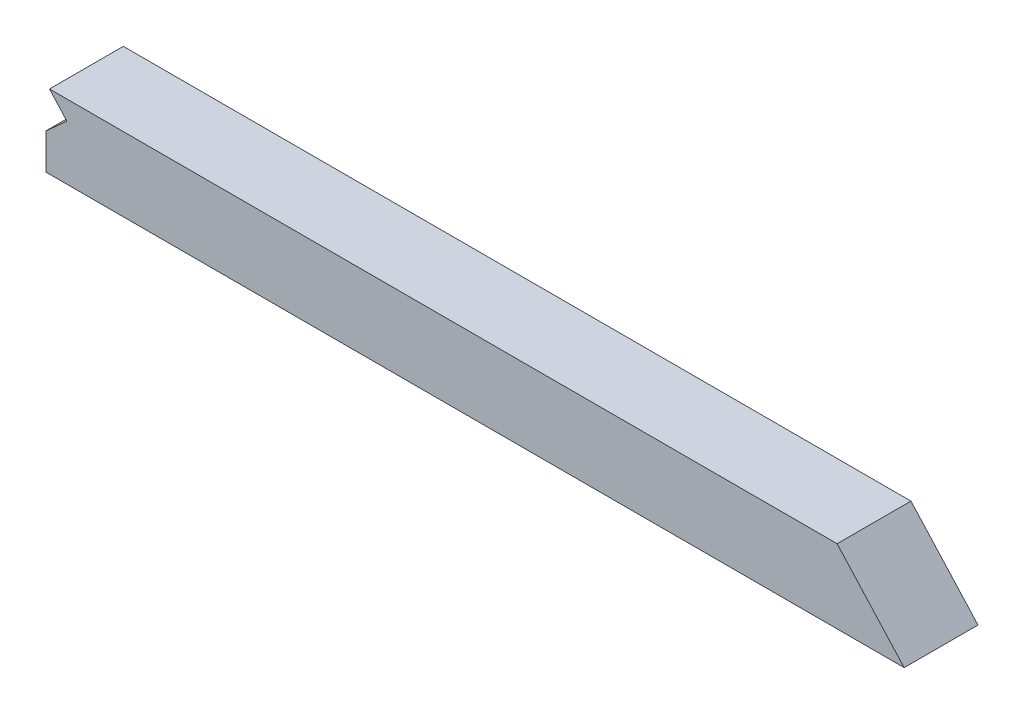
SolidWorks part; units mm, degrees
material "Pine"
ref_plane "X-Y Datum" through (0, 0, 0) normal (0, 0, 1) x (1, 0, 0)
ref_plane "X-Z Datum" through (0, 0, 0) normal (0, 1, 0) x (1, 0, 0)
ref_plane "Y-Z Datum" through (0, 0, 0) normal (1, 0, 0) x (0, 0, -1)
sketch "Sketch1" plane through (0, 0, 0) normal (1, 0, 0) x (0, 0, -1)
  line L1 (-19.05, 19.05) -> (19.05, 19.05)
  line L2 (-19.05, 19.05) -> (-19.05, -19.05)
  line L3 (-19.05, -19.05) -> (19.05, -19.05)
  line L4 (19.05, 19.05) -> (19.05, -19.05)
  line L5 (-19.05, 19.05) -> (19.05, -19.05) construction
  line L6 (-19.05, -19.05) -> (19.05, 19.05) construction
  point P0 (0, 0)
  dimension "D1" = 38.1
extrude "Boss-Extrude1" add sketch "Sketch1" along normal blind 442.976
sketch "Sketch2" plane through (0, 0, 19.05) normal (0, 0, 1) x (1, 0, 0)
  line L0 (442.976, -19.05) -> (408.3684, 19.05)
  line L1 (442.976, 19.05) -> (0, 19.05) construction
  line L5 (442.976, 19.05) -> (442.976, -19.05) construction
  line L6 (408.3684, 19.05) -> (442.976, 19.05)
  line L7 (442.976, 19.05) -> (442.976, -19.05)
  dimension "D1" = 42.25
extrude "Cut-Extrude1" cut sketch "Sketch2" against normal through all
sketch "Sketch3" plane through (0, 0, 19.05) normal (0, 0, 1) x (1, 0, 0)
  line L0 (0, -0.5694) -> (10.7563, 9.1215)
  line L1 (10.7563, 9.1215) -> (1.8112, 19.05)
  line L2 (408.3684, 19.05) -> (0, 19.05) construction
  line L3 (0, -0.5694) -> (1.8112, 19.05)
  line L4 (0, -0.5694) -> (0, 19.05)
  line L5 (0, 19.05) -> (1.8112, 19.05)
  line L6 (0, 19.05) -> (0, -19.05) construction
  point P3 (0, 0)
  point P8 (0, 0)
  point P9 (0, 0)
  point P11 (1.5988, -0.9315)
  point P12 (0, -0.5694)
  line M5 (408.3684, 19.05) -> (0, 19.05)
  line M6 (0, 19.05) -> (0, -19.05)
  dimension "D1" = 19.6194
  dimension "D2" = 14.478
  dimension "D3" = 132.017
extrude "Cut-Extrude2" cut sketch "Sketch3" against normal through all both contours L3 M6 M5 | L3 L0 L1
